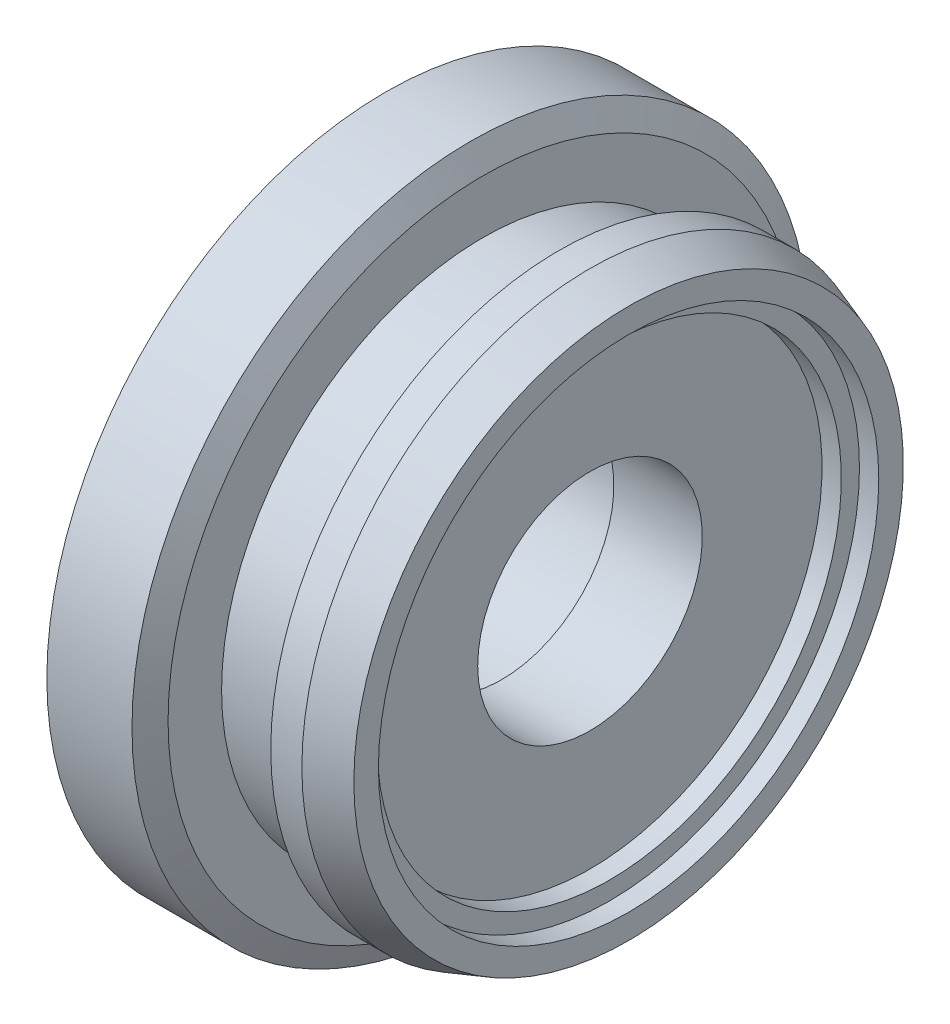
SolidWorks part; units mm, degrees
ref_plane "Front Plane" through (0, 0, 0) normal (0, 0, 1) x (1, 0, 0)
ref_plane "Top Plane" through (0, 0, 0) normal (0, 1, 0) x (1, 0, 0)
ref_plane "Right Plane" through (0, 0, 0) normal (1, 0, 0) x (0, 0, -1)
sketch "Sketch1" plane through (0, 0, 0) normal (0, 0, 1) x (1, 0, 0)
  line L0 (-3.5185, 27.9769) -> (-3.5185, 72.3212)
  line L1 (-3.5185, 72.3212) -> (14.6638, 72.3212)
  line L2 (14.6638, 72.3212) -> (17.3227, 67.2693)
  line L3 (17.3227, 67.2693) -> (17.3227, 55.8362)
  line L4 (17.3227, 55.8362) -> (33.5418, 55.8362)
  line L5 (33.5418, 55.8362) -> (33.5418, 61.5528)
  line L6 (33.5418, 61.5528) -> (40.1889, 61.5528)
  line L7 (40.1889, 61.5528) -> (48.4314, 58.6945)
  line L8 (48.4314, 58.6945) -> (48.4314, 53.4432)
  line L9 (48.4314, 53.4432) -> (44.3102, 53.4432)
  line L10 (44.3102, 53.4432) -> (44.3102, 49.5683)
  line L11 (44.3102, 49.5683) -> (40.1889, 49.5683)
  line L12 (40.1889, 49.5683) -> (40.1889, 23.99)
  line L13 (40.1889, 23.99) -> (21.3037, 23.99)
  line L14 (21.3037, 23.99) -> (19.2054, 27.9769)
  line L15 (19.2054, 27.9769) -> (-3.5185, 27.9769)
  line L16 (0, 0) -> (58.3453, 0) construction
revolve "Revolve1" add sketch "Sketch1" angle 360 about L16
